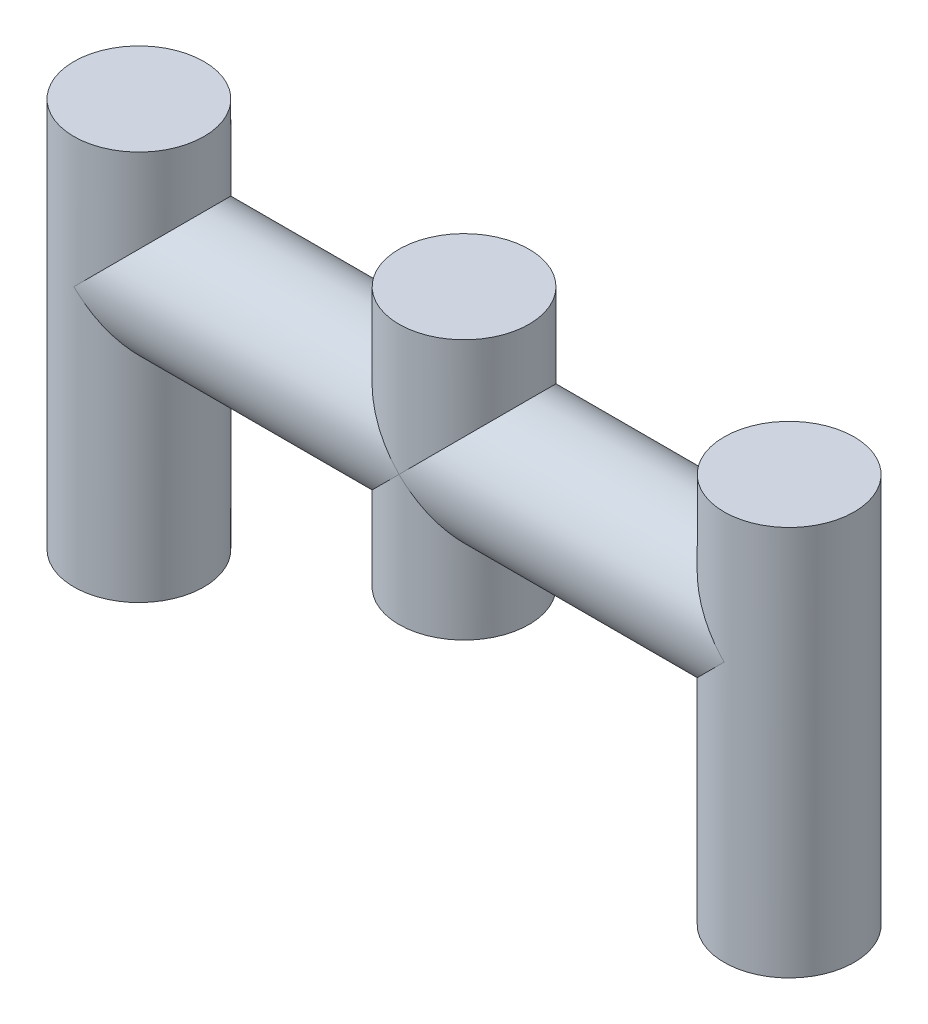
SolidWorks part; units mm, degrees
ref_plane "Front Plane" through (0, 0, 0) normal (0, 0, 1) x (1, 0, 0)
ref_plane "Top Plane" through (0, 0, 0) normal (0, 1, 0) x (1, 0, 0)
ref_plane "Right Plane" through (0, 0, 0) normal (1, 0, 0) x (0, 0, -1)
sketch "Sketch2" plane through (0, 0, 0) normal (0, 1, 0) x (1, 0, 0)
  circle A0 centre (0, 0) radius 2.5
  dimension "D1" = 5
extrude "Boss-Extrude2" add sketch "Sketch2" along normal blind 10
sketch "Sketch3" plane through (0, 0, 0) normal (1, 0, 0) x (0, 0, -1)
  line L0 (0, 0) -> (0, 10) construction
  line L1 (2.5, 10) -> (-2.5, 10) construction
  line L2 (-2.5, 5) -> (2.5, 5) construction
  line L3 (-2.5, 10) -> (-2.5, 0) construction
  line L4 (2.5, 0) -> (2.5, 10) construction
  circle A0 centre (0, 5) radius 2.5
  dimension "D1" = 5
extrude "Boss-Extrude3" add sketch "Sketch3" along normal blind 12.5
sketch "Sketch4" plane through (0, 0, 0) normal (0, 1, 0) x (1, 0, 0)
  line L0 (12.5, -2.5) -> (12.5, 2.5) construction
  line L1 (12.5, 2.5) -> (12.5, -2.5)
  arc A0 (12.5, 2.5) -> (12.5, -2.5) centre (12.5, 0) ccw
extrude "Boss-Extrude4" add sketch "Sketch4" along normal blind 10
mirror "Mirror5" about plane through (12.5, 5, 0) normal (1, 0, 0) of "Boss-Extrude4", "Boss-Extrude3", "Boss-Extrude2"
sketch "Sketch5" plane through (0, 0, 0) normal (0, -1, 0) x (1, 0, 0)
  circle A0 centre (0, 0) radius 2.5
  circle A1 centre (25, 0) radius 2.5
extrude "Boss-Extrude5" add sketch "Sketch5" along normal blind 5
